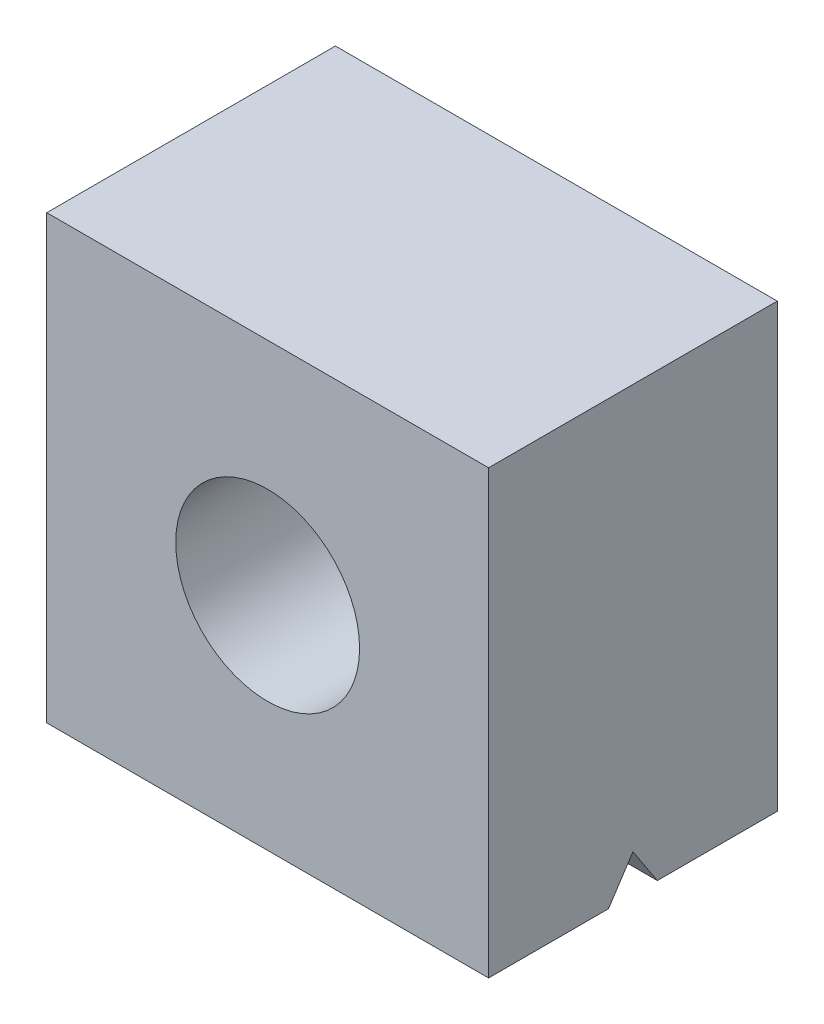
SolidWorks part; units mm, degrees
ref_plane "Front Plane" through (0, 0, 0) normal (0, 0, 1) x (1, 0, 0)
ref_plane "Top Plane" through (0, 0, 0) normal (0, 1, 0) x (1, 0, 0)
ref_plane "Right Plane" through (0, 0, 0) normal (1, 0, 0) x (0, 0, -1)
sketch "Sketch3" plane through (0, 0, 0) normal (0, 0, 1) x (1, 0, 0)
  line L1 (-9.525, 9.525) -> (9.525, 9.525)
  line L2 (-9.525, 9.525) -> (-9.525, -9.525)
  line L3 (-9.525, -9.525) -> (9.525, -9.525)
  line L4 (9.525, 9.525) -> (9.525, -9.525)
  line L5 (-9.525, 9.525) -> (9.525, -9.525) construction
  line L6 (-9.525, -9.525) -> (9.525, 9.525) construction
  point P0 (0, 0)
  dimension "D1" = 19.05
  dimension "D2" = 19.05
extrude "Boss-Extrude2" add sketch "Sketch3" along normal blind 12.446
sketch "Sketch4" plane through (0, 0, 12.446) normal (0, 0, 1) x (1, 0, 0)
  circle A0 centre (0, 0) radius 3.9624
  dimension "D1" = 7.9248
extrude "Cut-Extrude2" cut sketch "Sketch4" against normal through all
sketch "Sketch9" plane through (0, 0, 0) normal (1, 0, 0) x (0, 0, -1)
  line L0 (-7.2758, -9.525) -> (-6.223, -7.9248)
  line L1 (-12.446, -9.525) -> (0, -9.525) construction
  line L2 (-6.223, -7.9248) -> (-6.223, -9.6519) construction
  line L3 (-5.1702, -9.525) -> (-6.223, -7.9248)
  point P8 (-11.6977, 1.6451)
  dimension "D1" = 1.6002
  dimension "D2" = 6.223
extrude "Cut-Extrude3" cut sketch "Sketch9" against normal through all and the other way through all
